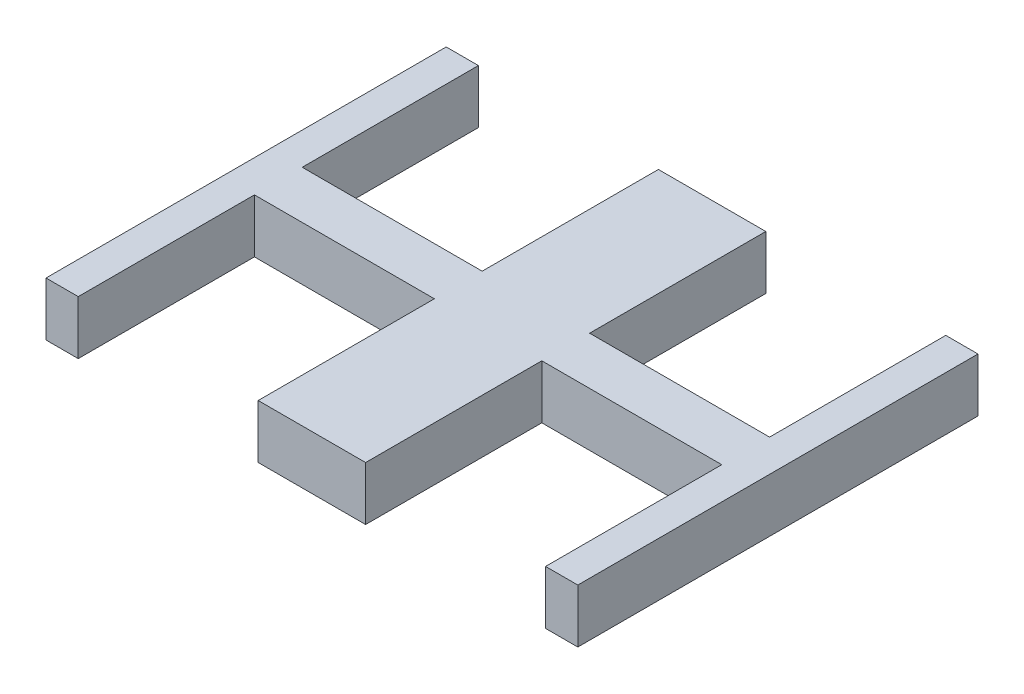
SolidWorks part; units mm, degrees
ref_plane "Front Plane" through (0, 0, 0) normal (0, 0, 1) x (1, 0, 0)
ref_plane "Top Plane" through (0, 0, 0) normal (0, 1, 0) x (1, 0, 0)
ref_plane "Right Plane" through (0, 0, 0) normal (1, 0, 0) x (0, 0, -1)
sketch "Sketch1" plane through (0, 0, 0) normal (0, 1, 0) x (1, 0, 0)
  line L1 (-9.9, 7.45) -> (9.9, 7.45)
  line L2 (-9.9, 7.45) -> (-9.9, -7.45)
  line L3 (-9.9, -7.45) -> (9.9, -7.45)
  line L4 (9.9, 7.45) -> (9.9, -7.45)
  line L5 (-9.9, 7.45) -> (9.9, -7.45) construction
  line L6 (-9.9, -7.45) -> (9.9, 7.45) construction
  point P0 (0, 0)
  dimension "D1" = 19.8
  dimension "D2" = 14.9
extrude "Boss-Extrude1" add sketch "Sketch1" along normal blind 2
sketch "Sketch2" plane through (0, 2, 0) normal (0, 1, 0) x (1, 0, 0)
  line L0 (-9.9, 7.45) -> (-9.9, -7.45) construction
  line L1 (-8.7, 7.45) -> (-2, 7.45)
  line L2 (-8.7, 7.45) -> (-8.7, 0.89)
  line L3 (-8.7, 0.89) -> (-2, 0.89)
  line L4 (-2, 7.45) -> (-2, 0.89)
  line L5 (8.7, -7.45) -> (2, -7.45)
  line L6 (9.9, 7.45) -> (-9.9, 7.45) construction
  line L7 (-2, -7.45) -> (-2, -0.89)
  line L8 (-8.7, -0.89) -> (-2, -0.89)
  line L9 (-8.7, -7.45) -> (-8.7, -0.89)
  line L10 (-8.7, -7.45) -> (-2, -7.45)
  line L11 (8.7, -7.45) -> (8.7, -0.89)
  line L12 (8.7, -0.89) -> (2, -0.89)
  line L13 (2, -7.45) -> (2, -0.89)
  line L14 (2, 7.45) -> (2, 0.89)
  line L15 (8.7, 0.89) -> (2, 0.89)
  line L16 (8.7, 7.45) -> (8.7, 0.89)
  line L17 (8.7, 7.45) -> (2, 7.45)
  line L18 (-9.9, -7.45) -> (9.9, -7.45) construction
  dimension "D1" = 6.7
  dimension "D2" = 6.56
  dimension "D3" = 1.2
  dimension "D4" = 0
  dimension "D5" = 0
  dimension "D6" = 0
  dimension "D7" = 0
extrude "Cut-Extrude2" cut sketch "Sketch2" against normal through all
